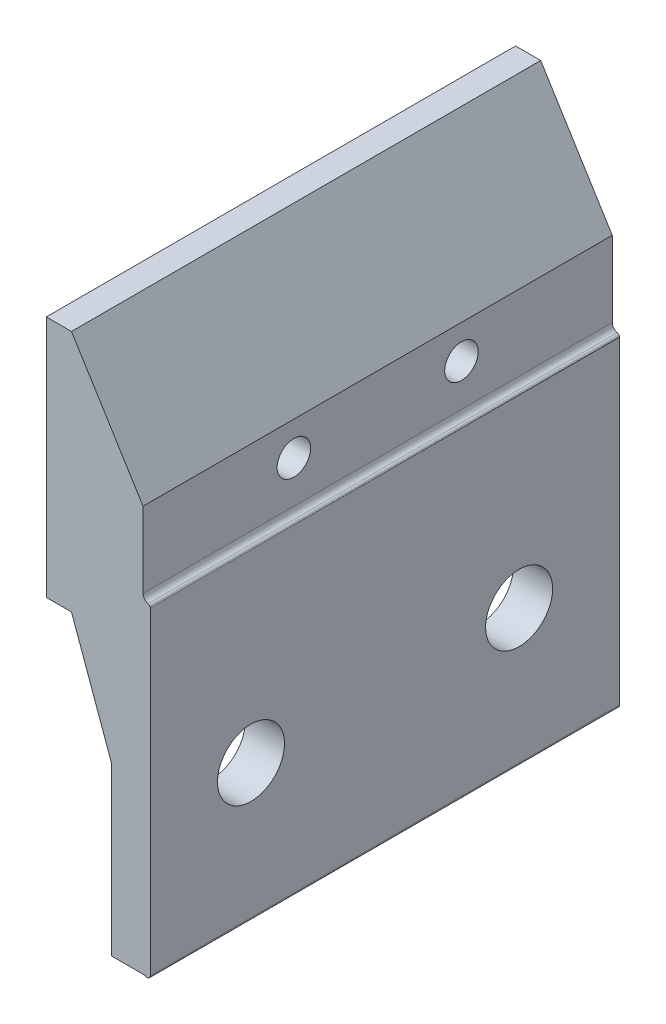
SolidWorks part; units mm, degrees
ref_plane "前视基准面" through (0, 0, 0) normal (0, 0, 1) x (1, 0, 0)
ref_plane "上视基准面" through (0, 0, 0) normal (0, 1, 0) x (1, 0, 0)
ref_plane "右视基准面" through (0, 0, 0) normal (1, 0, 0) x (0, 0, -1)
other "Configuration Table"
sketch "草图1" plane through (0, 0, 0) normal (0, 0, 1) x (1, 0, 0)
  line L0 (-15.8526, -15.4934) -> (-14.3526, -15.4934)
  line L1 (-14.3526, -15.4934) -> (-10.0826, -22.3915)
  line L2 (-10.0826, -22.3915) -> (-10.0826, -26.8915)
  line L3 (-9.6416, -27.4294) -> (-9.6416, -46.4294)
  line L4 (-9.9759, -46.5775) -> (-10.9759, -46.5775)
  line L5 (-15.8526, -15.4934) -> (-15.8526, -29.9934)
  line L6 (-11.9759, -36.5775) -> (-11.9759, -46.5775)
  line L7 (-11.9759, -46.5775) -> (-10.9759, -46.5775)
  line L8 (-15.8526, -29.9934) -> (-14.3526, -29.9934)
  line L9 (-14.3526, -29.9934) -> (-11.9759, -36.5775)
  arc A0 (-10.0826, -26.8915) -> (-9.7856, -27.278) centre (-9.6826, -26.8915) ccw
  arc A1 (-9.7856, -27.278) -> (-9.6416, -27.4294) centre (-9.8372, -27.4713) cw
  arc A2 (-9.6416, -46.4294) -> (-9.9759, -46.5775) centre (-9.8416, -46.4294) cw
  dimension "D1" = 14.5
  dimension "D5" = 0.2
  dimension "D7" = 0.2
  dimension "D8" = 0.4
  dimension "D2" = 10
  dimension "D3" = 1.5
  dimension "D4" = 7
  dimension "D6" = 19
  dimension "D9" = 4.5
  dimension "D10" = 1.5
  dimension "D11" = 1
  dimension "D12" = 1
extrude "凸台-拉伸2" add sketch "草图1" along normal blind 28
sketch "草图2" plane through (-10.0826, 0, 0) normal (1, 0, 0) x (0, 0, -1)
  line L0 (-28, -22.3915) -> (-19, -22.3915)
  line L1 (-28, -22.3915) -> (0, -22.3915) construction
  line L2 (-19, -22.3915) -> (-19, -24.3915)
  line L3 (-14, -1022.3915) -> (-14, 48977.6085) construction
  line L4 (-28, -46.4294) -> (-22, -46.4294)
  line L5 (-28, -46.4294) -> (0, -46.4294) construction
  line L6 (-22, -46.4294) -> (-22, -38.4294)
  circle A0 centre (-19, -24.3915) radius 1
  circle A1 centre (-22, -38.4294) radius 2
  circle A2 centre (-6, -38.4294) radius 2
  circle A3 centre (-9, -24.3915) radius 1
  point P9 (-14, -22.3915)
  dimension "D5" = 4
  dimension "D6" = 2
  dimension "D1" = 9
  dimension "D2" = 2
  dimension "D3" = 6
  dimension "D4" = 8
extrude "切除-拉伸3" cut sketch "草图2" against normal through all both and the other way through all
